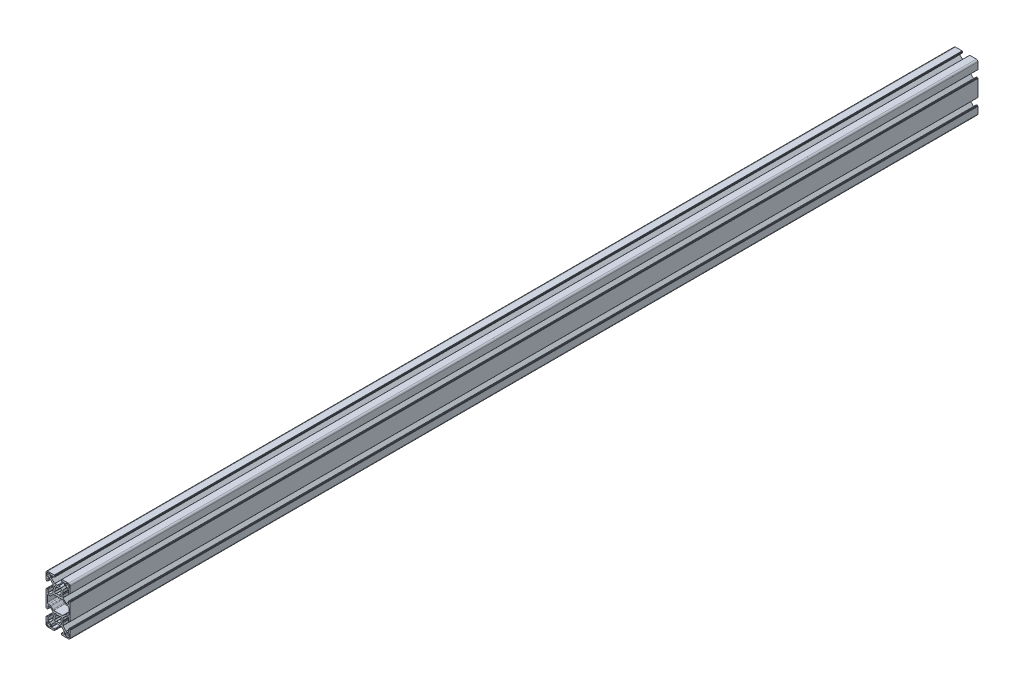
SolidWorks part; units mm, degrees
ref_plane "Front Plane" through (0, 0, 0) normal (0, 0, 1) x (1, 0, 0)
ref_plane "Top Plane" through (0, 0, 0) normal (0, 1, 0) x (1, 0, 0)
ref_plane "Right Plane" through (0, 0, 0) normal (1, 0, 0) x (0, 0, -1)
sketch "Sketch1" plane through (0, 0, 0) normal (0, 0, 1) x (1, 0, 0)
  line L0 (15.3348, -15) -> (-18.6959, -15) construction
  line L1 (-20.9994, 0) -> (26.1762, 0) construction
  line L2 (1.6001, -18.2806) -> (3.1547, -19.5053)
  line L3 (4.1172, -21) -> (0.9, -21)
  line L4 (4.35, -29.5) -> (4.25, -29.5)
  line L5 (4.05, -29.3) -> (4.05, -28.4)
  line L6 (4.55, -29.7) -> (4.55, -29.8)
  line L7 (0.9, -21) -> (0.1019, -20.5392)
  line L8 (1.6001, -11.7194) -> (3.1547, -10.4947)
  line L9 (3.2806, -13.3999) -> (4.5184, -11.8641)
  line L10 (3.2806, -16.6001) -> (4.5184, -18.1359)
  line L11 (6.0045, -19.1216) -> (6.0045, -15.9)
  line L12 (12.6, -23.25) -> (10.1328, -23.25)
  line L13 (10.5, -24.5) -> (12.7, -24.5)
  line L14 (12.7, -28.7) -> (10.5, -28.7)
  line L15 (15, -28) -> (15, -19.75)
  line L16 (13.7, -25.5) -> (13.7, -27.7)
  line L17 (14.8, -19.55) -> (14.7, -19.55)
  line L18 (14.5, -19.35) -> (14.5, -19.25)
  line L19 (14.3, -19.05) -> (13.4, -19.05)
  line L20 (12.8, -19.65) -> (12.8, -23.05)
  line L21 (8.25, -27.6) -> (8.25, -25.1328)
  line L22 (9.5, -27.7) -> (9.5, -25.5)
  line L23 (9.9914, -23.1914) -> (6.063, -19.263)
  line L24 (12.8, -10.35) -> (12.8, -6.95)
  line L25 (15, 10.25) -> (15, -10.25)
  line L26 (9.9914, -6.8086) -> (6.063, -10.737)
  line L27 (8.9272, -5.5393) -> (6.4104, -8.0562)
  line L28 (14.3, -10.95) -> (13.4, -10.95)
  line L29 (14.5, -10.65) -> (14.5, -10.75)
  line L30 (14.8, -10.45) -> (14.7, -10.45)
  line L31 (6.0045, -10.8784) -> (6.0045, -14.1)
  line L32 (6.0045, -15.9) -> (5.5426, -15.1)
  line L33 (6.0045, -14.1) -> (5.5426, -14.9)
  line L34 (12.6, -6.75) -> (10.1328, -6.75)
  line L35 (11.85, -5.1) -> (9.9879, -5.1)
  line L36 (13.35, 3.6) -> (13.35, -3.6)
  line L37 (4.75, -30) -> (13, -30)
  line L38 (8.1914, -24.9914) -> (4.2586, -21.0586)
  line L39 (4.65, -27.8) -> (8.05, -27.8)
  line L40 (-1.6001, 18.2806) -> (-3.1547, 19.5053)
  line L41 (-4.1172, 21) -> (-0.9, 21)
  line L42 (-4.35, 29.5) -> (-4.25, 29.5)
  line L43 (-4.05, 29.3) -> (-4.05, 28.4)
  line L44 (-4.55, 29.7) -> (-4.55, 29.8)
  line L45 (-0.9, 21) -> (-0.1019, 20.5392)
  line L46 (-1.6001, 11.7194) -> (-3.1547, 10.4947)
  line L47 (-5.3497, 8.4955) -> (5.3497, 8.4955)
  line L48 (-3.2806, 13.3999) -> (-4.5184, 11.8641)
  line L49 (-3.2806, 16.6001) -> (-4.5184, 18.1359)
  line L50 (-6.0045, 19.1216) -> (-6.0045, 15.9)
  line L51 (-12.6, 23.25) -> (-10.1328, 23.25)
  line L52 (-10.5, 24.5) -> (-12.7, 24.5)
  line L53 (-12.7, 28.7) -> (-10.5, 28.7)
  line L54 (-15, 28) -> (-15, 19.75)
  line L55 (-13.7, 25.5) -> (-13.7, 27.7)
  line L56 (-14.8, 19.55) -> (-14.7, 19.55)
  line L57 (-14.5, 19.35) -> (-14.5, 19.25)
  line L58 (-14.3, 19.05) -> (-13.4, 19.05)
  line L59 (-12.8, 19.65) -> (-12.8, 23.05)
  line L60 (-8.25, 27.6) -> (-8.25, 25.1328)
  line L61 (-9.5, 27.7) -> (-9.5, 25.5)
  line L62 (-9.9914, 23.1914) -> (-6.063, 19.263)
  line L63 (-12.8, 10.35) -> (-12.8, 6.95)
  line L64 (-9.9914, 6.8086) -> (-6.063, 10.737)
  line L65 (-8.9272, 5.5393) -> (-6.4104, 8.0562)
  line L66 (-14.3, 10.95) -> (-13.4, 10.95)
  line L67 (-14.5, 10.65) -> (-14.5, 10.75)
  line L68 (-14.8, 10.45) -> (-14.7, 10.45)
  line L69 (-6.0045, 10.8784) -> (-6.0045, 14.1)
  line L70 (-6.0045, 15.9) -> (-5.5426, 15.1)
  line L71 (-6.0045, 14.1) -> (-5.5426, 14.9)
  line L72 (-12.6, 6.75) -> (-10.1328, 6.75)
  line L73 (-11.85, 5.1) -> (-9.9879, 5.1)
  line L74 (-4.75, 30) -> (-13, 30)
  line L75 (-8.1914, 24.9914) -> (-4.2586, 21.0586)
  line L76 (-4.65, 27.8) -> (-8.05, 27.8)
  line L77 (4.65, 27.8) -> (8.05, 27.8)
  line L78 (8.1914, 24.9914) -> (4.2586, 21.0586)
  line L79 (4.75, 30) -> (13, 30)
  line L80 (11.85, 5.1) -> (9.9879, 5.1)
  line L81 (12.6, 6.75) -> (10.1328, 6.75)
  line L82 (6.0045, 14.1) -> (5.5426, 14.9)
  line L83 (6.0045, 15.9) -> (5.5426, 15.1)
  line L84 (6.0045, 10.8784) -> (6.0045, 14.1)
  line L85 (14.8, 10.45) -> (14.7, 10.45)
  line L86 (14.5, 10.65) -> (14.5, 10.75)
  line L87 (14.3, 10.95) -> (13.4, 10.95)
  line L88 (8.9272, 5.5393) -> (6.4104, 8.0562)
  line L89 (9.9914, 6.8086) -> (6.063, 10.737)
  line L90 (12.8, 10.35) -> (12.8, 6.95)
  line L91 (9.9914, 23.1914) -> (6.063, 19.263)
  line L92 (9.5, 27.7) -> (9.5, 25.5)
  line L93 (8.25, 27.6) -> (8.25, 25.1328)
  line L94 (12.8, 19.65) -> (12.8, 23.05)
  line L95 (14.3, 19.05) -> (13.4, 19.05)
  line L96 (14.5, 19.35) -> (14.5, 19.25)
  line L97 (14.8, 19.55) -> (14.7, 19.55)
  line L98 (13.7, 25.5) -> (13.7, 27.7)
  line L99 (15, 28) -> (15, 19.75)
  line L100 (12.7, 28.7) -> (10.5, 28.7)
  line L101 (10.5, 24.5) -> (12.7, 24.5)
  line L102 (12.6, 23.25) -> (10.1328, 23.25)
  line L103 (6.0045, 19.1216) -> (6.0045, 15.9)
  line L104 (3.2806, 16.6001) -> (4.5184, 18.1359)
  line L105 (3.2806, 13.3999) -> (4.5184, 11.8641)
  line L106 (1.6001, 11.7194) -> (3.1547, 10.4947)
  line L107 (0.9, 21) -> (0.1019, 20.5392)
  line L108 (4.55, 29.7) -> (4.55, 29.8)
  line L109 (4.05, 29.3) -> (4.05, 28.4)
  line L110 (4.35, 29.5) -> (4.25, 29.5)
  line L111 (4.1172, 21) -> (0.9, 21)
  line L112 (1.6001, 18.2806) -> (3.1547, 19.5053)
  line L155 (0, 26.7355) -> (0, -34.1789) construction
  line L156 (-4.65, -27.8) -> (-8.05, -27.8)
  line L157 (-8.1914, -24.9914) -> (-4.2586, -21.0586)
  line L158 (-4.75, -30) -> (-13, -30)
  line L162 (-13.35, 3.6) -> (-13.35, -3.6)
  line L163 (-11.85, -5.1) -> (-9.9879, -5.1)
  line L164 (-12.6, -6.75) -> (-10.1328, -6.75)
  line L165 (-6.0045, -14.1) -> (-5.5426, -14.9)
  line L166 (-6.0045, -15.9) -> (-5.5426, -15.1)
  line L167 (-6.0045, -10.8784) -> (-6.0045, -14.1)
  line L168 (-14.8, -10.45) -> (-14.7, -10.45)
  line L169 (-14.5, -10.65) -> (-14.5, -10.75)
  line L170 (-14.3, -10.95) -> (-13.4, -10.95)
  line L171 (-8.9272, -5.5393) -> (-6.4104, -8.0562)
  line L172 (-9.9914, -6.8086) -> (-6.063, -10.737)
  line L173 (-15, 10.25) -> (-15, -10.25)
  line L174 (-12.8, -10.35) -> (-12.8, -6.95)
  line L176 (-9.9914, -23.1914) -> (-6.063, -19.263)
  line L177 (-9.5, -27.7) -> (-9.5, -25.5)
  line L178 (-8.25, -27.6) -> (-8.25, -25.1328)
  line L179 (-12.8, -19.65) -> (-12.8, -23.05)
  line L180 (-14.3, -19.05) -> (-13.4, -19.05)
  line L181 (-14.5, -19.35) -> (-14.5, -19.25)
  line L182 (-14.8, -19.55) -> (-14.7, -19.55)
  line L183 (-13.7, -25.5) -> (-13.7, -27.7)
  line L184 (-15, -28) -> (-15, -19.75)
  line L185 (-12.7, -28.7) -> (-10.5, -28.7)
  line L186 (-10.5, -24.5) -> (-12.7, -24.5)
  line L187 (-12.6, -23.25) -> (-10.1328, -23.25)
  line L188 (-6.0045, -19.1216) -> (-6.0045, -15.9)
  line L214 (-3.2806, -16.6001) -> (-4.5184, -18.1359)
  line L215 (-3.2806, -13.3999) -> (-4.5184, -11.8641)
  line L216 (-5.3497, -8.4955) -> (5.3497, -8.4955)
  line L217 (-1.6001, -11.7194) -> (-3.1547, -10.4947)
  line L226 (-0.9, -21) -> (-0.1019, -20.5392)
  line L234 (-4.55, -29.7) -> (-4.55, -29.8)
  line L235 (-4.05, -29.3) -> (-4.05, -28.4)
  line L236 (-4.35, -29.5) -> (-4.25, -29.5)
  line L237 (-4.1172, -21) -> (-0.9, -21)
  line L238 (-1.6001, -18.2806) -> (-3.1547, -19.5053)
  arc A0 (4.5184, -18.1359) -> (3.1547, -19.5053) centre (0, -15) cw
  arc A1 (4.35, -29.5) -> (4.55, -29.7) centre (4.35, -29.7) cw
  arc A2 (4.25, -29.5) -> (4.05, -29.3) centre (4.25, -29.3) cw
  arc A3 (4.75, -30) -> (4.55, -29.8) centre (4.75, -29.8) cw
  arc A4 (4.05, -28.4) -> (4.65, -27.8) centre (4.65, -28.4) cw
  arc A5 (4.1172, -21) -> (4.2586, -21.0586) centre (4.1172, -21.2) cw
  arc A6 (3.2806, -13.3999) -> (3.2806, -16.6001) centre (0, -15) cw
  arc A7 (3.1547, -10.4947) -> (4.5184, -11.8641) centre (0, -15) cw
  arc A8 (12.6, -6.75) -> (12.8, -6.95) centre (12.6, -6.95) cw
  arc A9 (13.35, -3.6) -> (11.85, -5.1) centre (11.85, -3.6) cw
  arc A10 (9.9914, -6.8086) -> (10.1328, -6.75) centre (10.1328, -6.95) cw
  arc A11 (8.9272, -5.5393) -> (9.9879, -5.1) centre (9.9879, -6.6) cw
  arc A12 (15, -28) -> (13, -30) centre (13, -28) cw
  arc A13 (12.7, -24.5) -> (13.7, -25.5) centre (12.7, -25.5) cw
  arc A14 (13.7, -27.7) -> (12.7, -28.7) centre (12.7, -27.7) cw
  arc A15 (14.7, -19.55) -> (14.5, -19.35) centre (14.7, -19.35) cw
  arc A16 (14.8, -19.55) -> (15, -19.75) centre (14.8, -19.75) cw
  arc A17 (14.3, -19.05) -> (14.5, -19.25) centre (14.3, -19.25) cw
  arc A18 (12.8, -19.65) -> (13.4, -19.05) centre (13.4, -19.65) cw
  arc A19 (12.8, -23.05) -> (12.6, -23.25) centre (12.6, -23.05) cw
  arc A20 (9.5, -25.5) -> (10.5, -24.5) centre (10.5, -25.5) cw
  arc A21 (8.1914, -24.9914) -> (8.25, -25.1328) centre (8.05, -25.1328) cw
  arc A22 (8.25, -27.6) -> (8.05, -27.8) centre (8.05, -27.6) cw
  arc A23 (10.5, -28.7) -> (9.5, -27.7) centre (10.5, -27.7) cw
  arc A24 (10.1328, -23.25) -> (9.9914, -23.1914) centre (10.1328, -23.05) cw
  arc A25 (6.063, -19.263) -> (6.0045, -19.1216) centre (6.2045, -19.1216) cw
  arc A26 (14.5, -10.75) -> (14.3, -10.95) centre (14.3, -10.75) cw
  arc A27 (15, -10.25) -> (14.8, -10.45) centre (14.8, -10.25) cw
  arc A28 (14.5, -10.65) -> (14.7, -10.45) centre (14.7, -10.65) cw
  arc A29 (13.4, -10.95) -> (12.8, -10.35) centre (13.4, -10.35) cw
  arc A30 (5.5426, -15.1) -> (5.5426, -14.9) centre (5.7158, -15) cw
  arc A31 (6.0045, -10.8784) -> (6.063, -10.737) centre (6.2045, -10.8784) cw
  arc A32 (6.4104, -8.0562) -> (5.3497, -8.4955) centre (5.3497, -6.9955) cw
  arc A33 (-1.6001, 18.2806) -> (1.6001, 18.2806) centre (0, 15) cw
  arc A34 (1.6001, 11.7194) -> (-1.6001, 11.7194) centre (0, 15) cw
  arc A35 (-4.5184, 18.1359) -> (-3.1547, 19.5053) centre (0, 15) cw
  arc A36 (-4.35, 29.5) -> (-4.55, 29.7) centre (-4.35, 29.7) cw
  arc A37 (-4.25, 29.5) -> (-4.05, 29.3) centre (-4.25, 29.3) cw
  arc A38 (-4.75, 30) -> (-4.55, 29.8) centre (-4.75, 29.8) cw
  arc A39 (-4.05, 28.4) -> (-4.65, 27.8) centre (-4.65, 28.4) cw
  arc A40 (-4.1172, 21) -> (-4.2586, 21.0586) centre (-4.1172, 21.2) cw
  arc A41 (0.1019, 20.5392) -> (-0.1019, 20.5392) centre (0, 20.7158) cw
  arc A42 (-3.2806, 13.3999) -> (-3.2806, 16.6001) centre (0, 15) cw
  arc A43 (-3.1547, 10.4947) -> (-4.5184, 11.8641) centre (0, 15) cw
  arc A44 (-12.6, 6.75) -> (-12.8, 6.95) centre (-12.6, 6.95) cw
  arc A45 (-13.35, 3.6) -> (-11.85, 5.1) centre (-11.85, 3.6) cw
  arc A46 (-9.9914, 6.8086) -> (-10.1328, 6.75) centre (-10.1328, 6.95) cw
  arc A47 (-8.9272, 5.5393) -> (-9.9879, 5.1) centre (-9.9879, 6.6) cw
  arc A48 (-15, 28) -> (-13, 30) centre (-13, 28) cw
  arc A49 (-12.7, 24.5) -> (-13.7, 25.5) centre (-12.7, 25.5) cw
  arc A50 (-13.7, 27.7) -> (-12.7, 28.7) centre (-12.7, 27.7) cw
  arc A51 (-14.7, 19.55) -> (-14.5, 19.35) centre (-14.7, 19.35) cw
  arc A52 (-14.8, 19.55) -> (-15, 19.75) centre (-14.8, 19.75) cw
  arc A53 (-14.3, 19.05) -> (-14.5, 19.25) centre (-14.3, 19.25) cw
  arc A54 (-12.8, 19.65) -> (-13.4, 19.05) centre (-13.4, 19.65) cw
  arc A55 (-12.8, 23.05) -> (-12.6, 23.25) centre (-12.6, 23.05) cw
  arc A56 (-9.5, 25.5) -> (-10.5, 24.5) centre (-10.5, 25.5) cw
  arc A57 (-8.1914, 24.9914) -> (-8.25, 25.1328) centre (-8.05, 25.1328) cw
  arc A58 (-8.25, 27.6) -> (-8.05, 27.8) centre (-8.05, 27.6) cw
  arc A59 (-10.5, 28.7) -> (-9.5, 27.7) centre (-10.5, 27.7) cw
  arc A60 (-10.1328, 23.25) -> (-9.9914, 23.1914) centre (-10.1328, 23.05) cw
  arc A61 (-6.063, 19.263) -> (-6.0045, 19.1216) centre (-6.2045, 19.1216) cw
  arc A62 (-14.5, 10.75) -> (-14.3, 10.95) centre (-14.3, 10.75) cw
  arc A63 (-15, 10.25) -> (-14.8, 10.45) centre (-14.8, 10.25) cw
  arc A64 (-14.5, 10.65) -> (-14.7, 10.45) centre (-14.7, 10.65) cw
  arc A65 (-13.4, 10.95) -> (-12.8, 10.35) centre (-13.4, 10.35) cw
  arc A66 (-5.5426, 15.1) -> (-5.5426, 14.9) centre (-5.7158, 15) cw
  arc A67 (-6.0045, 10.8784) -> (-6.063, 10.737) centre (-6.2045, 10.8784) cw
  arc A68 (-6.4104, 8.0562) -> (-5.3497, 8.4955) centre (-5.3497, 6.9955) cw
  arc A69 (6.4104, 8.0562) -> (5.3497, 8.4955) centre (5.3497, 6.9955) ccw
  arc A70 (6.0045, 10.8784) -> (6.063, 10.737) centre (6.2045, 10.8784) ccw
  arc A71 (5.5426, 15.1) -> (5.5426, 14.9) centre (5.7158, 15) ccw
  arc A72 (13.4, 10.95) -> (12.8, 10.35) centre (13.4, 10.35) ccw
  arc A73 (14.5, 10.65) -> (14.7, 10.45) centre (14.7, 10.65) ccw
  arc A74 (15, 10.25) -> (14.8, 10.45) centre (14.8, 10.25) ccw
  arc A75 (14.5, 10.75) -> (14.3, 10.95) centre (14.3, 10.75) ccw
  arc A76 (6.063, 19.263) -> (6.0045, 19.1216) centre (6.2045, 19.1216) ccw
  arc A77 (10.1328, 23.25) -> (9.9914, 23.1914) centre (10.1328, 23.05) ccw
  arc A78 (10.5, 28.7) -> (9.5, 27.7) centre (10.5, 27.7) ccw
  arc A79 (8.25, 27.6) -> (8.05, 27.8) centre (8.05, 27.6) ccw
  arc A80 (8.1914, 24.9914) -> (8.25, 25.1328) centre (8.05, 25.1328) ccw
  arc A81 (9.5, 25.5) -> (10.5, 24.5) centre (10.5, 25.5) ccw
  arc A82 (12.8, 23.05) -> (12.6, 23.25) centre (12.6, 23.05) ccw
  arc A83 (12.8, 19.65) -> (13.4, 19.05) centre (13.4, 19.65) ccw
  arc A84 (14.3, 19.05) -> (14.5, 19.25) centre (14.3, 19.25) ccw
  arc A85 (14.8, 19.55) -> (15, 19.75) centre (14.8, 19.75) ccw
  arc A86 (14.7, 19.55) -> (14.5, 19.35) centre (14.7, 19.35) ccw
  arc A87 (13.7, 27.7) -> (12.7, 28.7) centre (12.7, 27.7) ccw
  arc A88 (12.7, 24.5) -> (13.7, 25.5) centre (12.7, 25.5) ccw
  arc A89 (15, 28) -> (13, 30) centre (13, 28) ccw
  arc A90 (8.9272, 5.5393) -> (9.9879, 5.1) centre (9.9879, 6.6) ccw
  arc A91 (9.9914, 6.8086) -> (10.1328, 6.75) centre (10.1328, 6.95) ccw
  arc A92 (13.35, 3.6) -> (11.85, 5.1) centre (11.85, 3.6) ccw
  arc A93 (12.6, 6.75) -> (12.8, 6.95) centre (12.6, 6.95) ccw
  arc A94 (3.1547, 10.4947) -> (4.5184, 11.8641) centre (0, 15) ccw
  arc A95 (3.2806, 13.3999) -> (3.2806, 16.6001) centre (0, 15) ccw
  arc A96 (4.1172, 21) -> (4.2586, 21.0586) centre (4.1172, 21.2) ccw
  arc A97 (4.05, 28.4) -> (4.65, 27.8) centre (4.65, 28.4) ccw
  arc A98 (4.75, 30) -> (4.55, 29.8) centre (4.75, 29.8) ccw
  arc A99 (4.25, 29.5) -> (4.05, 29.3) centre (4.25, 29.3) ccw
  arc A100 (4.35, 29.5) -> (4.55, 29.7) centre (4.35, 29.7) ccw
  arc A101 (4.5184, 18.1359) -> (3.1547, 19.5053) centre (0, 15) ccw
  arc A138 (-6.4104, -8.0562) -> (-5.3497, -8.4955) centre (-5.3497, -6.9955) ccw
  arc A140 (-6.0045, -10.8784) -> (-6.063, -10.737) centre (-6.2045, -10.8784) ccw
  arc A141 (-5.5426, -15.1) -> (-5.5426, -14.9) centre (-5.7158, -15) ccw
  arc A142 (-13.4, -10.95) -> (-12.8, -10.35) centre (-13.4, -10.35) ccw
  arc A143 (-14.5, -10.65) -> (-14.7, -10.45) centre (-14.7, -10.65) ccw
  arc A144 (-15, -10.25) -> (-14.8, -10.45) centre (-14.8, -10.25) ccw
  arc A145 (-14.5, -10.75) -> (-14.3, -10.95) centre (-14.3, -10.75) ccw
  arc A147 (-6.063, -19.263) -> (-6.0045, -19.1216) centre (-6.2045, -19.1216) ccw
  arc A148 (-10.1328, -23.25) -> (-9.9914, -23.1914) centre (-10.1328, -23.05) ccw
  arc A149 (-10.5, -28.7) -> (-9.5, -27.7) centre (-10.5, -27.7) ccw
  arc A150 (-8.25, -27.6) -> (-8.05, -27.8) centre (-8.05, -27.6) ccw
  arc A151 (-8.1914, -24.9914) -> (-8.25, -25.1328) centre (-8.05, -25.1328) ccw
  arc A152 (-9.5, -25.5) -> (-10.5, -24.5) centre (-10.5, -25.5) ccw
  arc A153 (-12.8, -23.05) -> (-12.6, -23.25) centre (-12.6, -23.05) ccw
  arc A154 (-12.8, -19.65) -> (-13.4, -19.05) centre (-13.4, -19.65) ccw
  arc A155 (-14.3, -19.05) -> (-14.5, -19.25) centre (-14.3, -19.25) ccw
  arc A156 (-14.8, -19.55) -> (-15, -19.75) centre (-14.8, -19.75) ccw
  arc A157 (-14.7, -19.55) -> (-14.5, -19.35) centre (-14.7, -19.35) ccw
  arc A158 (-13.7, -27.7) -> (-12.7, -28.7) centre (-12.7, -27.7) ccw
  arc A159 (-12.7, -24.5) -> (-13.7, -25.5) centre (-12.7, -25.5) ccw
  arc A160 (-15, -28) -> (-13, -30) centre (-13, -28) ccw
  arc A184 (-8.9272, -5.5393) -> (-9.9879, -5.1) centre (-9.9879, -6.6) ccw
  arc A185 (-9.9914, -6.8086) -> (-10.1328, -6.75) centre (-10.1328, -6.95) ccw
  arc A186 (-13.35, -3.6) -> (-11.85, -5.1) centre (-11.85, -3.6) ccw
  arc A187 (-12.6, -6.75) -> (-12.8, -6.95) centre (-12.6, -6.95) ccw
  arc A188 (-3.1547, -10.4947) -> (-4.5184, -11.8641) centre (0, -15) ccw
  arc A189 (-3.2806, -13.3999) -> (-3.2806, -16.6001) centre (0, -15) ccw
  arc A198 (0.1019, -20.5392) -> (-0.1019, -20.5392) centre (0, -20.7158) ccw
  arc A203 (-4.1172, -21) -> (-4.2586, -21.0586) centre (-4.1172, -21.2) ccw
  arc A204 (-4.05, -28.4) -> (-4.65, -27.8) centre (-4.65, -28.4) ccw
  arc A205 (-4.75, -30) -> (-4.55, -29.8) centre (-4.75, -29.8) ccw
  arc A206 (-4.25, -29.5) -> (-4.05, -29.3) centre (-4.25, -29.3) ccw
  arc A207 (-4.35, -29.5) -> (-4.55, -29.7) centre (-4.35, -29.7) ccw
  arc A208 (-4.5184, -18.1359) -> (-3.1547, -19.5053) centre (0, -15) ccw
  arc A261 (1.6001, -11.7194) -> (-1.6001, -11.7194) centre (0, -15) ccw
  arc A263 (-1.6001, -18.2806) -> (1.6001, -18.2806) centre (0, -15) ccw
  point P178 (0, -8.4955)
  point P382 (0, 8.4955)
  point P385 (-15, 0)
  point P387 (-13.35, 0)
  point P388 (13.35, 0)
  point P390 (15, 0)
  dimension "D7" = 7.3
  dimension "D9" = 11
  dimension "D1" = 30
  dimension "D2" = 60
  dimension "D3" = 8.1
  dimension "D4" = 9
  dimension "D5" = 30
  dimension "D6" = 8.1
  dimension "D8" = 15
  dimension "D10" = 16.5
  dimension "D11" = 16.5
extrude "Extrude1" add sketch "Sketch1" along normal blind 1128.95
